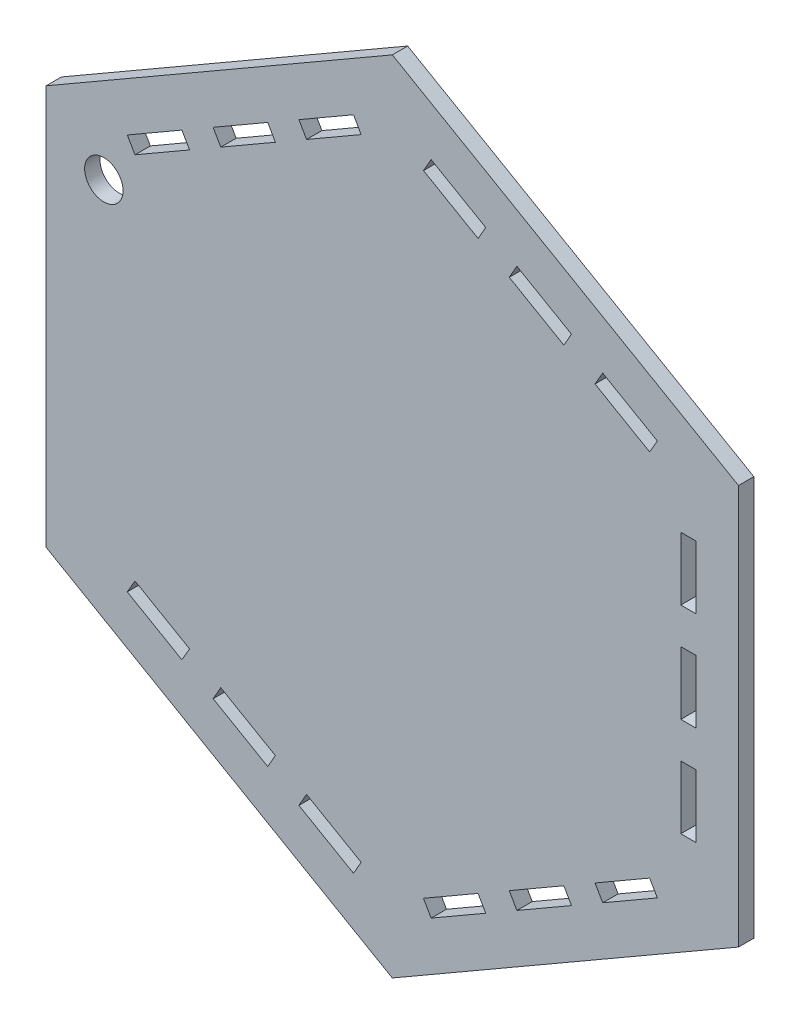
SolidWorks part; units mm, degrees
ref_plane "Alzado" through (0, 0, 0) normal (0, 0, 1) x (1, 0, 0)
ref_plane "Planta" through (0, 0, 0) normal (0, 1, 0) x (1, 0, 0)
ref_plane "Vista lateral" through (0, 0, 0) normal (1, 0, 0) x (0, 0, -1)
sketch "Croquis1" plane through (0, 0, 0) normal (0, 0, 1) x (1, 0, 0)
  line L0 (94.1087, 36.1149) -> (147.9805, 129.4235) construction
  line L1 (105.5186, 94.5274) -> (107.4623, 97.8939) construction
  line L2 (101.6813, 100.207) -> (100.1926, 97.6024)
  line L7 (100.1926, 97.6024) -> (110.8447, 91.4524)
  line L115 (110.8447, 91.4524) -> (112.3334, 94.057)
  line L122 (112.3334, 94.057) -> (101.6813, 100.207)
  line L151 (135.1757, 80.869) -> (145.8279, 74.719)
  line L188 (133.6644, 78.2774) -> (135.1757, 80.869)
  line L189 (144.3166, 72.1274) -> (133.6644, 78.2774)
  line L198 (145.8279, 74.719) -> (144.3166, 72.1274)
  line L199 (94.1087, 36.1149) -> (206.0582, 36.1149) construction
  line L200 (133.6644, -6.0476) -> (135.1757, -8.6391)
  line L201 (94.1087, 114.1149) -> (26.5588, 75.1149)
  line L202 (26.5588, 75.1149) -> (26.5588, -2.8851)
  line L203 (26.5588, -2.8851) -> (94.1087, -41.8851)
  line L204 (94.1087, -41.8851) -> (161.6587, -2.8851)
  line L205 (161.6587, -2.8851) -> (161.6587, 75.1149)
  line L206 (161.6587, 75.1149) -> (94.1087, 114.1149)
  line L207 (94.1087, 101.1149) -> (37.8171, 68.6149) construction
  line L208 (37.8171, 68.6149) -> (37.8171, 3.6149) construction
  line L209 (37.8171, 3.6149) -> (94.1087, -28.8851) construction
  line L210 (94.1087, -28.8851) -> (150.4004, 3.6149) construction
  line L211 (150.4004, 3.6149) -> (150.4004, 68.6149) construction
  line L212 (150.4004, 68.6149) -> (94.1087, 101.1149) construction
  line L216 (94.1087, 114.1149) -> (94.1087, 101.1149) construction
  line L217 (150.4004, 68.6149) -> (161.6587, 75.1149)
  line L218 (118.4172, 90.5445) -> (116.9285, 87.9399)
  line L219 (116.9285, 87.9399) -> (127.5806, 81.7899)
  line L220 (127.5806, 81.7899) -> (129.0693, 84.3945)
  line L221 (129.0693, 84.3945) -> (118.4172, 90.5445)
  line L222 (144.3166, 0.1024) -> (133.6644, -6.0476)
  line L223 (145.8279, -2.4891) -> (144.3166, 0.1024)
  line L224 (135.1757, -8.6391) -> (145.8279, -2.4891)
  line L225 (129.0693, -12.1647) -> (118.4172, -18.3147)
  line L226 (127.5806, -9.5601) -> (129.0693, -12.1647)
  line L227 (116.9285, -15.7101) -> (127.5806, -9.5601)
  line L228 (118.4172, -18.3147) -> (116.9285, -15.7101)
  line L229 (112.3334, -21.8272) -> (101.6813, -27.9772)
  line L230 (110.8447, -19.2226) -> (112.3334, -21.8272)
  line L231 (100.1926, -25.3726) -> (110.8447, -19.2226)
  line L232 (101.6813, -27.9772) -> (100.1926, -25.3726)
  line L233 (77.3728, -19.2226) -> (75.8841, -21.8272)
  line L234 (88.0249, -25.3726) -> (77.3728, -19.2226)
  line L235 (86.5362, -27.9772) -> (88.0249, -25.3726)
  line L236 (75.8841, -21.8272) -> (86.5362, -27.9772)
  line L237 (60.6369, -9.5601) -> (59.1482, -12.1647)
  line L238 (71.289, -15.7101) -> (60.6369, -9.5601)
  line L239 (69.8003, -18.3147) -> (71.289, -15.7101)
  line L240 (59.1482, -12.1647) -> (69.8003, -18.3147)
  line L241 (43.9009, 0.1024) -> (54.553, -6.0476)
  line L242 (42.3896, -2.4891) -> (43.9009, 0.1024)
  line L243 (53.0417, -8.6391) -> (42.3896, -2.4891)
  line L244 (54.553, -6.0476) -> (53.0417, -8.6391)
  line L245 (54.553, 78.2774) -> (53.0417, 80.869)
  line L246 (43.9009, 72.1274) -> (54.553, 78.2774)
  line L247 (42.3896, 74.719) -> (43.9009, 72.1274)
  line L248 (53.0417, 80.869) -> (42.3896, 74.719)
  line L249 (59.1482, 84.3945) -> (69.8003, 90.5445)
  line L250 (60.6369, 81.7899) -> (59.1482, 84.3945)
  line L251 (71.289, 87.9399) -> (60.6369, 81.7899)
  line L252 (69.8003, 90.5445) -> (71.289, 87.9399)
  line L253 (75.8841, 94.057) -> (86.5362, 100.207)
  line L254 (77.3728, 91.4524) -> (75.8841, 94.057)
  line L255 (88.0249, 97.6024) -> (77.3728, 91.4524)
  line L256 (86.5362, 100.207) -> (88.0249, 97.6024)
  line L261 (150.4004, 61.5899) -> (153.4004, 61.5899)
  line L262 (150.4004, 42.2649) -> (153.4004, 42.2649)
  line L263 (150.4004, 42.2649) -> (150.4004, 29.9649)
  line L264 (150.4004, 29.9649) -> (153.4004, 29.9649)
  line L265 (153.4004, 42.2649) -> (153.4004, 29.9649)
  line L266 (150.4004, 42.2649) -> (153.4004, 29.9649) construction
  line L267 (150.4004, 29.9649) -> (153.4004, 42.2649) construction
  line L268 (150.4004, 61.5899) -> (150.4004, 49.2899)
  line L269 (150.4004, 49.2899) -> (153.4004, 49.2899)
  line L270 (153.4004, 61.5899) -> (153.4004, 49.2899)
  line L271 (150.4004, 55.4399) -> (170.1624, 55.4399) construction
  line L272 (150.4004, 10.6399) -> (150.4004, 22.9399)
  line L273 (150.4004, 22.9399) -> (153.4004, 22.9399)
  line L274 (153.4004, 10.6399) -> (153.4004, 22.9399)
  line L275 (150.4004, 10.6399) -> (153.4004, 10.6399)
  circle A4 centre (37.8171, 64.8649) radius 3.75
  circle A12 centre (94.1087, 36.1149) radius 67.55 construction
  circle A13 centre (94.1087, 36.1149) radius 56.2917 construction
  point P67 (151.9004, 36.1149)
  dimension "D7" = 0
  dimension "D12" = 12.2999
  dimension "D19" = 7.5
  dimension "D2" = 6.15
  dimension "D3" = 26.35
  dimension "D4" = 26.35
  dimension "D5" = 6.15
  dimension "D6" = 13.175
  dimension "D8" = 12.3
  dimension "D9" = 3
  dimension "D10" = 0
  dimension "D11" = 65
  dimension "D13" = 3
  dimension "D14" = 0
  dimension "D15" = 0
  dimension "D16" = 12.3
  dimension "D17" = 78
  dimension "D18" = 13.175
extrude "Saliente-Extruir1" add sketch "Croquis1" along normal blind 3
